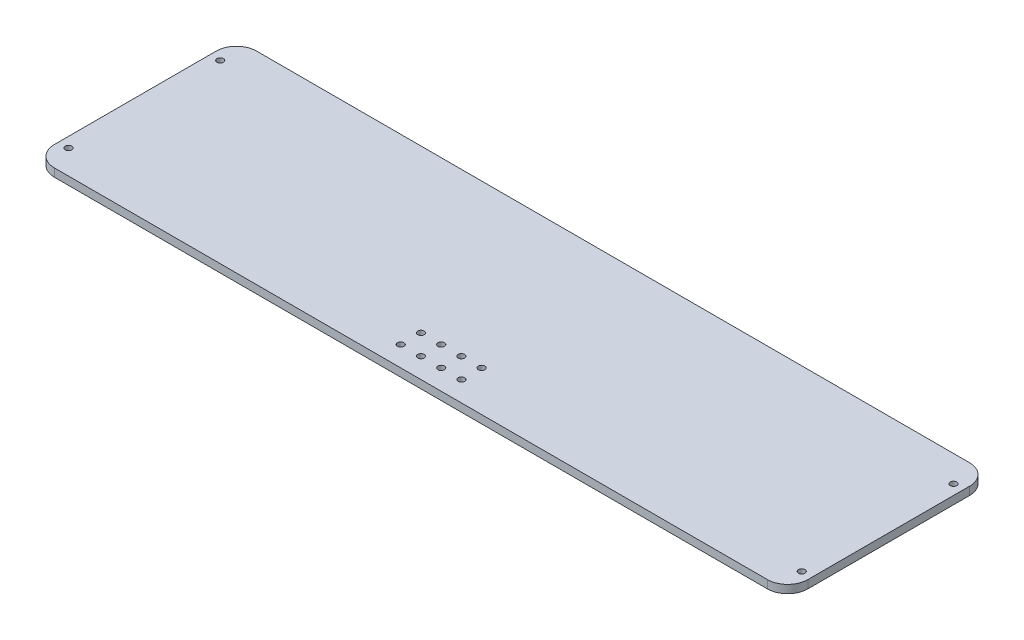
SolidWorks part; units mm, degrees
ref_plane "前视基准面" through (0, 0, 0) normal (0, 0, 1) x (1, 0, 0)
ref_plane "上视基准面" through (0, 0, 0) normal (0, 1, 0) x (1, 0, 0)
ref_plane "右视基准面" through (0, 0, 0) normal (1, 0, 0) x (0, 0, -1)
other "Configuration Table"
sketch "草图1" plane through (0, 0, 0) normal (0, 1, 0) x (1, 0, 0)
  line L0 (0, 0) -> (0, 36.4916) construction
  line L1 (-176.25, 50) -> (176.25, 50)
  line L2 (-186.25, 40) -> (-186.25, -40)
  line L3 (-176.25, -50) -> (176.25, -50)
  line L4 (186.25, 40) -> (186.25, -40)
  line L5 (-186.25, 50) -> (186.25, -50) construction
  line L6 (-186.25, -50) -> (186.25, 50) construction
  circle A0 centre (181.25, -38) radius 1.6
  circle A1 centre (181.25, 37) radius 1.6
  circle A2 centre (-181.25, -38) radius 1.6
  circle A3 centre (-181.25, 37) radius 1.6
  arc A4 (-186.25, -40) -> (-176.25, -50) centre (-176.25, -40) ccw
  arc A5 (176.25, -50) -> (186.25, -40) centre (176.25, -40) ccw
  arc A6 (176.25, 50) -> (186.25, 40) centre (176.25, 40) cw
  arc A7 (-176.25, 50) -> (-186.25, 40) centre (-176.25, 40) ccw
  point P0 (0, 0)
  dimension "D3" = 12
  dimension "D5" = 3.2
  dimension "D6" = 3.2
  dimension "D8" = 10
  dimension "D1" = 372.5
  dimension "D2" = 100
  dimension "D4" = 75
  dimension "D7" = 5
extrude "凸台-拉伸1" add sketch "草图1" along normal blind 4
sketch "草图2" plane through (0, 4, 0) normal (0, 1, 0) x (1, 0, 0)
  line L0 (-176.25, -50) -> (176.25, -50) construction
  line L1 (-15, -30) -> (15, -30) construction
  line L2 (-15, -30) -> (-15, -40) construction
  line L3 (-15, -40) -> (15, -40) construction
  line L4 (15, -30) -> (15, -40) construction
  line L5 (-15, -30) -> (15, -40) construction
  line L6 (-15, -40) -> (15, -30) construction
  circle A0 centre (-15, -30) radius 1.6
  circle A1 centre (15, -30) radius 1.6
  circle A2 centre (15, -40) radius 1.6
  circle A3 centre (-15, -40) radius 1.6
  circle A4 centre (-5, -30) radius 1.6
  circle A5 centre (5, -30) radius 1.6
  circle A6 centre (-5, -40) radius 1.6
  circle A7 centre (5, -40) radius 1.6
  point P0 (0, -35)
  dimension "D4" = 3.2
  dimension "D5" = 3.2
  dimension "D6" = 3.2
  dimension "D7" = 3.2
  dimension "D10" = 10
  dimension "D1" = 30
  dimension "D2" = 10
  dimension "D3" = 15
  dimension "D11" = 10
  dimension "D8" = 3
  dimension "D9" = 3
extrude "切除-拉伸1" cut sketch "草图2" against normal blind 3
